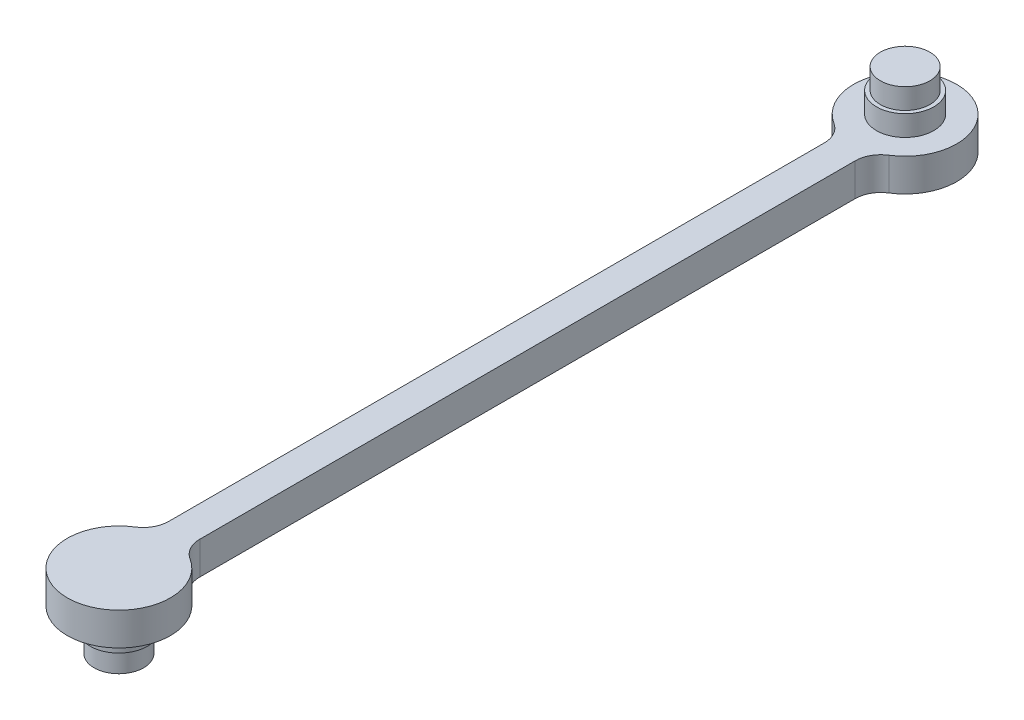
SolidWorks part; units mm, degrees
ref_plane "Front Plane" through (0, 0, 0) normal (0, 0, 1) x (1, 0, 0)
ref_plane "Top Plane" through (0, 0, 0) normal (0, 1, 0) x (1, 0, 0)
ref_plane "Right Plane" through (0, 0, 0) normal (1, 0, 0) x (0, 0, -1)
sketch "Sketch1" plane through (0, 0, 0) normal (0, 1, 0) x (1, 0, 0)
  line L1 (0, 0) -> (6, 0)
  line L2 (0, 0) -> (0, 152.4)
  line L3 (0, 152.4) -> (6, 152.4)
  line L4 (6, 0) -> (6, 152.4)
  circle A0 centre (3, 152.4) radius 10
  circle A2 centre (3, 0) radius 10
  point P9 (0, 0)
  dimension "D4" = 20
  dimension "D6" = 20
  dimension "D1" = 152.4
  dimension "D2" = 6
  dimension "D3" = 3
  dimension "D5" = 0
  dimension "D7" = 0
  dimension "D8" = 3
extrude "Boss-Extrude1" add sketch "Sketch1" along normal blind 6.35 contours L2 A2 L4 L1 | L4 A2 L2 L1 | A2 L4 A0 L2 | L2 A0 L4 L3 | L4 A0 L2 L3
sketch "Sketch2" plane through (0, 6.35, 0) normal (0, 1, 0) x (1, 0, 0)
  circle A0 centre (3, 152.4) radius 5.5562
  arc A3 (6, 142.8606) -> (0, 142.8606) centre (3, 152.4) ccw construction
  point P2 (0, 0)
  dimension "D1" = 11.1125
  dimension "D3" = 0
extrude "Boss-Extrude2" add sketch "Sketch2" along normal blind 4
sketch "Sketch4" plane through (0, 10.35, 0) normal (0, 1, 0) x (1, 0, 0)
  circle A0 centre (3, 152.4) radius 4.805
  circle A1 centre (3, 152.4) radius 5.5562 construction
  dimension "D1" = 9.61
  dimension "D2" = 0
extrude "Boss-Extrude3" add sketch "Sketch4" along normal blind 4
sketch "Sketch5" plane through (0, 0, 0) normal (0, -1, 0) x (1, 0, 0)
  circle A0 centre (3, 0) radius 5.5563
  arc A2 (6, -9.5394) -> (0, -9.5394) centre (3, 0) ccw construction
  dimension "D1" = 11.1125
  dimension "D2" = 0
extrude "Boss-Extrude4" add sketch "Sketch5" along normal blind 4
sketch "Sketch6" plane through (0, -4, 0) normal (0, -1, 0) x (1, 0, 0)
  circle A0 centre (3, 0) radius 4.805
  circle A1 centre (3, 0) radius 5.5563 construction
  dimension "D1" = 0
  dimension "D2" = 9.61
extrude "Boss-Extrude5" add sketch "Sketch6" along normal blind 4
fillet "Fillet1" radius 5 4 edges at (6, 3.175, -142.8606) (0, 3.175, -142.8606) (0, 3.175, -9.5394) (6, 3.175, -9.5394)
